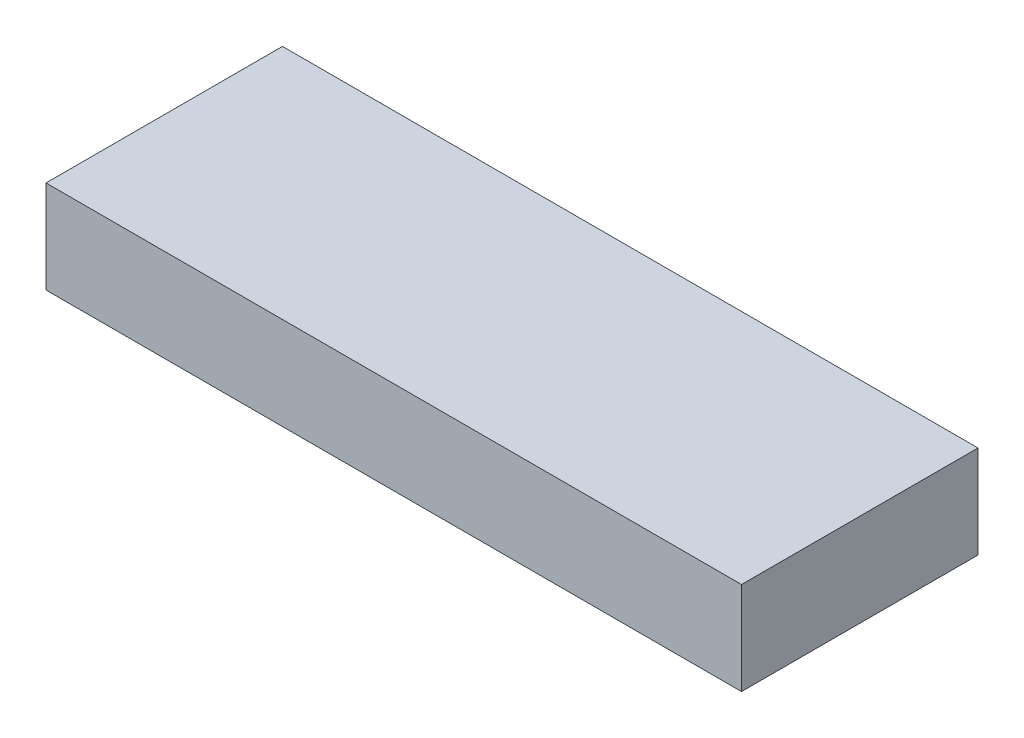
SolidWorks part; units mm, degrees
material "Balsa"
ref_plane "Plan de face" through (0, 0, 0) normal (0, 0, 1) x (1, 0, 0)
ref_plane "Plan de dessus" through (0, 0, 0) normal (0, 1, 0) x (1, 0, 0)
ref_plane "Plan de droite" through (0, 0, 0) normal (1, 0, 0) x (0, 0, -1)
sketch "Sketch1" plane through (0, 0, 0) normal (0, 1, 0) x (1, 0, 0)
  line L1 (-75, -25.5) -> (75, -25.5)
  line L2 (-75, -25.5) -> (-75, 25.5)
  line L3 (-75, 25.5) -> (75, 25.5)
  line L4 (75, -25.5) -> (75, 25.5)
  line L5 (-75, -25.5) -> (75, 25.5) construction
  line L6 (-75, 25.5) -> (75, -25.5) construction
  point P0 (0, 0)
  dimension "D1" = 51
  dimension "D2" = 150
extrude "Boss-Extrude1" add sketch "Sketch1" along normal blind 20
